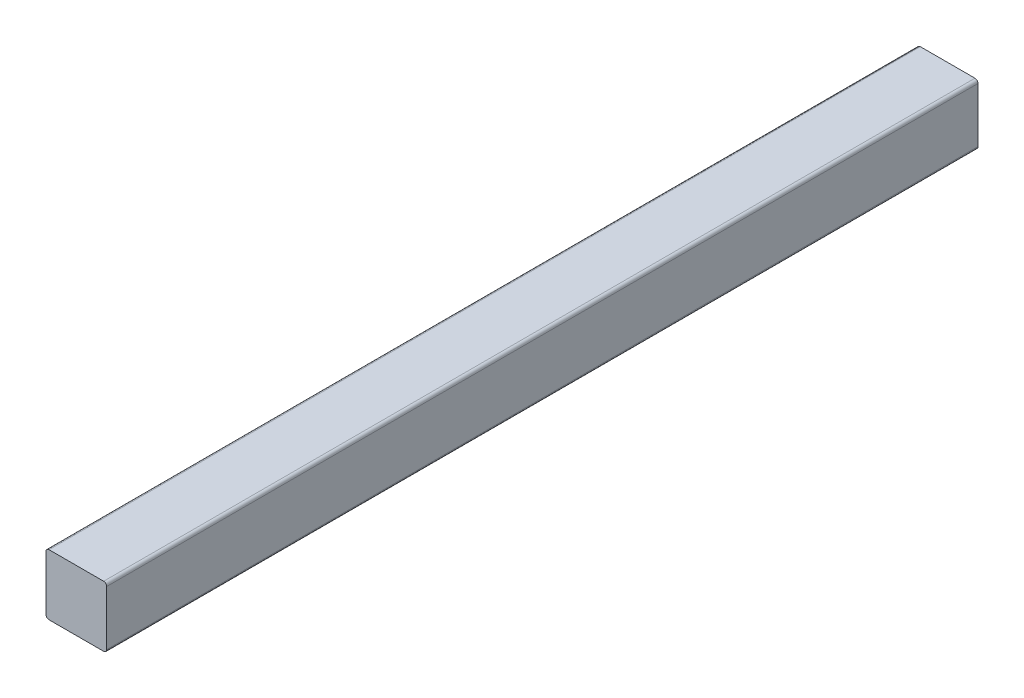
SolidWorks part; units mm, degrees
ref_plane "正面" through (0, 0, 0) normal (0, 0, 1) x (1, 0, 0)
ref_plane "平面" through (0, 0, 0) normal (0, 1, 0) x (1, 0, 0)
ref_plane "右側面" through (0, 0, 0) normal (1, 0, 0) x (0, 0, -1)
sketch "ｽｹｯﾁ1" plane through (0, 0, 0) normal (0, 0, 1) x (1, 0, 0)
  line L1 (-10, 10) -> (10, 10)
  line L2 (-10, 10) -> (-10, -10)
  line L3 (-10, -10) -> (10, -10)
  line L4 (10, 10) -> (10, -10)
  dimension "D1" = 10
  dimension "D2" = 10
  dimension "D3" = 20
  dimension "D4" = 20
extrude "ﾎﾞｽ - 押し出し1" add sketch "ｽｹｯﾁ1" along normal mid plane 287
fillet "ﾌｨﾚｯﾄ1" radius 1 4 edges at (-10, -10, 0) (10, -10, 0) (-10, 10, 0) (10, 10, 0)
